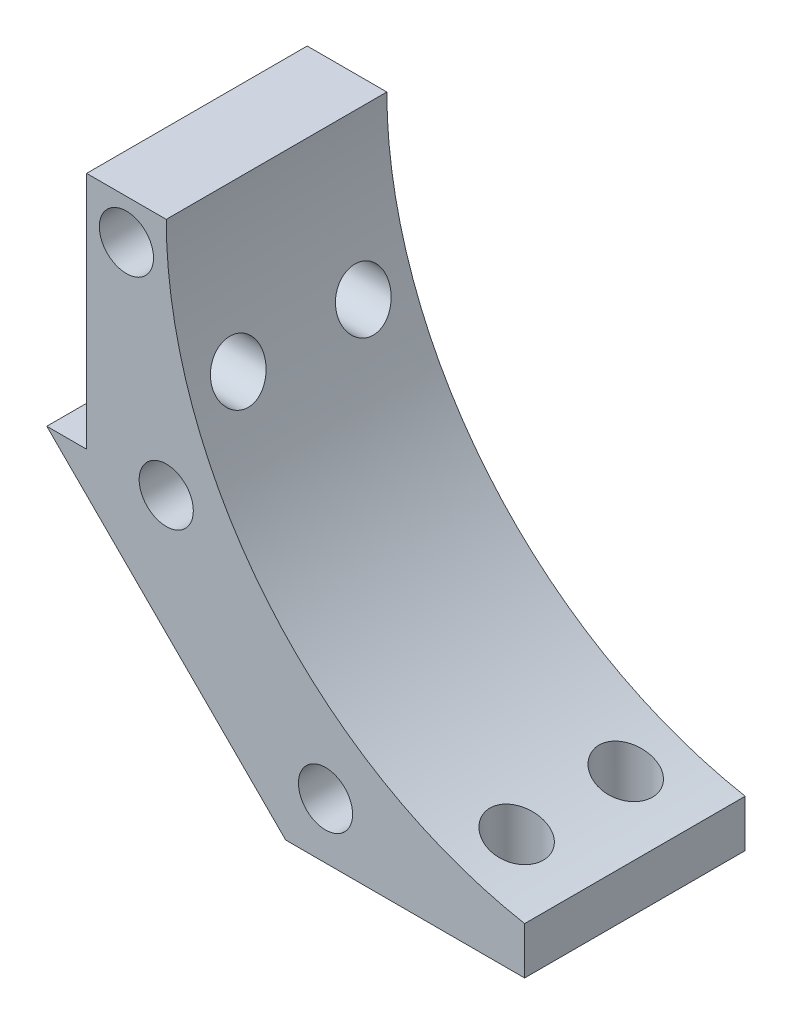
SolidWorks part; units mm, degrees
ref_plane "前视基准面" through (0, 0, 0) normal (0, 0, 1) x (1, 0, 0)
ref_plane "上视基准面" through (0, 0, 0) normal (0, 1, 0) x (1, 0, 0)
ref_plane "右视基准面" through (0, 0, 0) normal (1, 0, 0) x (0, 0, -1)
other "Configuration Table"
sketch "草图1" plane through (0, 0, 0) normal (0, 0, 1) x (1, 0, 0)
  line L0 (0, 30) -> (30, 0)
  line L1 (0, 0) -> (30, 0)
  line L2 (0, 0) -> (0, 30)
  line L3 (0, 30) -> (30, 30)
  line L4 (30, 0) -> (30, 30)
  line L6 (30, 30) -> (60, 30)
  line L7 (30, 30) -> (30, 0)
  line L8 (30, 0) -> (60, 0)
  line L9 (60, 30) -> (60, 0)
  line L10 (5, 30) -> (30, 30)
  line L11 (5, 30) -> (5, 60)
  line L12 (5, 60) -> (30, 60)
  line L13 (30, 30) -> (30, 60)
  dimension "D1" = 30
  dimension "D2" = 30
  dimension "D3" = 30
  dimension "D4" = 30
  dimension "D5" = 5
extrude "凸台-拉伸1" add sketch "草图1" along normal blind 27.7 contours L0 L4 L3 | L7 L6 L9 L8 | L11 L10 L13 L12
sketch "草图3" plane through (0, 0, 27.7) normal (0, 0, 1) x (1, 0, 0)
  line L0 (30, 0) -> (60, 0) construction
  line L1 (0, 30) -> (0, 105.7176) construction
  line L6 (0, 30) -> (30, 0)
  line L7 (30, 0) -> (60, 0)
  line L8 (60, 0) -> (60, 30)
  line L9 (5, 30) -> (0, 30)
  line L10 (0, 30) -> (30, 0)
  line L11 (30, 0) -> (60, 0)
  line L12 (60, 0) -> (60, 30)
  line L13 (5, 30) -> (0, 30)
  line L18 (60, 30) -> (30, 30)
  line L19 (60, 30) -> (30, 30)
  line L20 (30, 30) -> (30, 60)
  line L21 (30, 30) -> (30, 60)
  line L22 (30, 60) -> (5, 60)
  line L23 (30, 60) -> (5, 60)
  line L24 (5, 60) -> (5, 30)
  line L25 (5, 60) -> (5, 30)
  circle A0 centre (70, 60) radius 55
  line M4 (5, 30) -> (0, 30)
  dimension "D1" = 110
  dimension "D2" = 60
  dimension "D3" = 70
  dimension "D4" = 0
extrude "切除-拉伸1" cut sketch "草图3" against normal blind 40 contours A0 L12 M4
sketch "草图4" plane through (0, 0, 27.7) normal (0, 0, 1) x (1, 0, 0)
  line L6 (15, 60) -> (5, 60)
  line L7 (5, 60) -> (5, 30)
  line L8 (5, 30) -> (0, 30)
  line L9 (0, 30) -> (30, 0)
  line L10 (30, 0) -> (60, 0)
  line L11 (60, 0) -> (60, 5.9167)
  line L12 (15, 60) -> (5, 60)
  line L13 (5, 60) -> (5, 30)
  line L14 (5, 30) -> (0, 30)
  line L15 (0, 30) -> (30, 0)
  line L16 (30, 0) -> (60, 0)
  line L17 (60, 0) -> (60, 5.9167)
  arc A1 (15, 60) -> (60, 5.9167) centre (70, 60) ccw
  arc A2 (15, 60) -> (60, 5.9167) centre (70, 60) ccw
  circle A3 centre (35, 7) radius 3.4
  circle A4 centre (10, 55) radius 3.4
  circle A5 centre (15, 30) radius 3.4
  dimension "D2" = 6.8
  dimension "D3" = 30
  dimension "D4" = 6.8
  dimension "D5" = 6.8
  dimension "D9" = 25
  dimension "D10" = 7
  dimension "D6" = 5
  dimension "D7" = 5
  dimension "D8" = 10
  dimension "D1" = 0
extrude "切除-拉伸2" cut sketch "草图4" against normal through all contours A4 | A5 | A3
sketch "草图5" plane through (5, 0, 0) normal (-1, 0, 0) x (0, 0, 1)
  line L0 (27.7, 30) -> (0, 30) construction
  line L1 (27.7, 30) -> (27.7, 60) construction
  line L2 (0, 30) -> (0, 60) construction
  circle A0 centre (6, 42) radius 3.3
  circle A1 centre (21.7, 42) radius 3.3
  dimension "D1" = 6.6
  dimension "D2" = 6.6
  dimension "D3" = 12
  dimension "D4" = 12
  dimension "D5" = 6
  dimension "D6" = 6
extrude "切除-拉伸3" cut sketch "草图5" against normal through all
sketch "草图6" plane through (0, 0, 0) normal (0, -1, 0) x (1, 0, 0)
  line L0 (60, 27.7) -> (60, 0) construction
  line L1 (30, 27.7) -> (60, 27.7) construction
  line L2 (30, 0) -> (60, 0) construction
  circle A0 centre (52, 20.7) radius 3.35
  circle A1 centre (52, 7) radius 3.35
  dimension "D3" = 6.7
  dimension "D4" = 6.7
  dimension "D1" = 8
  dimension "D2" = 8
  dimension "D5" = 7
  dimension "D6" = 7
extrude "切除-拉伸4" cut sketch "草图6" against normal through all
move or copy body "实体-移动/复制1" [suppressed] bodies to move or copy 110 parameters "D1"=0, "D2"=0, "D3"=0
